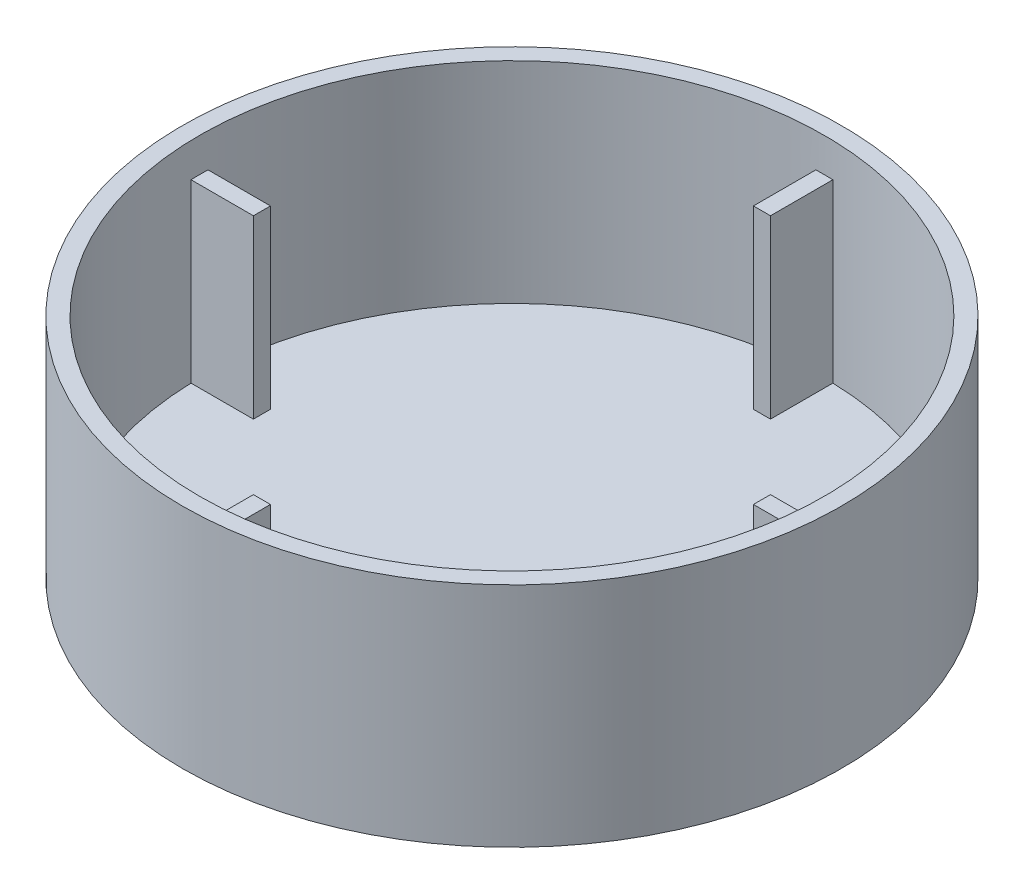
SolidWorks part; units mm, degrees
ref_plane "Front Plane" through (0, 0, 0) normal (0, 0, 1) x (1, 0, 0)
ref_plane "Top Plane" through (0, 0, 0) normal (0, 1, 0) x (1, 0, 0)
ref_plane "Right Plane" through (0, 0, 0) normal (1, 0, 0) x (0, 0, -1)
sketch "Sketch1" plane through (0, 0, 0) normal (0, 1, 0) x (1, 0, 0)
  circle A0 centre (0, 0) radius 29
  dimension "D1" = 58
extrude "Boss-Extrude1" add sketch "Sketch1" along normal blind 20
shell "Shell1" thickness 1.5
sketch "Sketch2" plane through (0, 1.5, 0) normal (0, 1, 0) x (1, 0, 0)
  line L0 (0, 0) -> (0, 22) construction
  line L1 (-0.75, 22) -> (0.75, 22)
  line L2 (-0.75, 22) -> (-0.75, 28.0878)
  line L3 (-0.75, 28.0878) -> (0.75, 28.0878)
  line L4 (0.75, 22) -> (0.75, 28.0878)
  line L5 (22, 0.75) -> (28.0878, 0.75)
  line L6 (22, -0.75) -> (28.0878, -0.75)
  line L7 (28.0878, 0.75) -> (28.0878, -0.75)
  line L8 (22, 0.75) -> (22, -0.75)
  line L9 (0.75, -22) -> (0.75, -28.0878)
  line L10 (-0.75, -22) -> (-0.75, -28.0878)
  line L11 (0.75, -28.0878) -> (-0.75, -28.0878)
  line L12 (0.75, -22) -> (-0.75, -22)
  line L13 (-22, -0.75) -> (-28.0878, -0.75)
  line L14 (-22, 0.75) -> (-28.0878, 0.75)
  line L15 (-28.0878, -0.75) -> (-28.0878, 0.75)
  line L16 (-22, -0.75) -> (-22, 0.75)
  point P22 (0, 0)
  dimension "D1" = 1.5
  dimension "D2" = 22
  dimension "D3" = 4
extrude "Boss-Extrude2" add sketch "Sketch2" along normal offset from surface (15.5 mm away) 3 up to face at (0, 20, 27.5)
